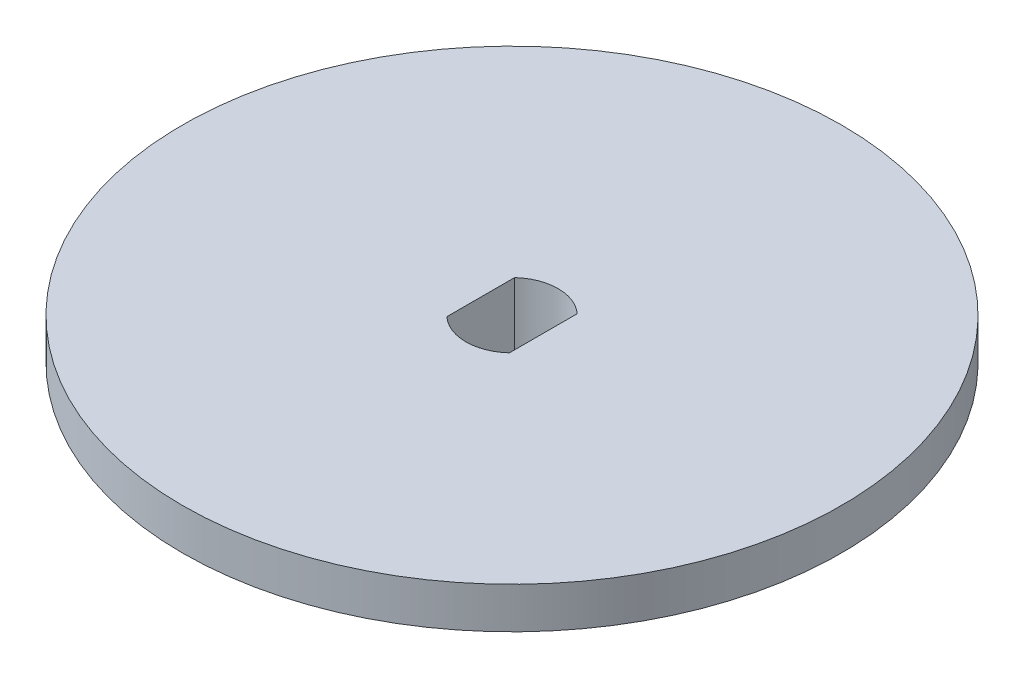
SolidWorks part; units mm, degrees
ref_plane "Front Plane" through (0, 0, 0) normal (0, 0, 1) x (1, 0, 0)
ref_plane "Top Plane" through (0, 0, 0) normal (0, 1, 0) x (1, 0, 0)
ref_plane "Right Plane" through (0, 0, 0) normal (1, 0, 0) x (0, 0, -1)
sketch "Sketch1" plane through (0, 0, 0) normal (0, 1, 0) x (1, 0, 0)
  line L0 (1.9, 2.0567) -> (1.9, -2.0567)
  line L1 (-1.9, -2.0567) -> (-1.9, 2.0567)
  line L2 (-1.9, 2.0567) -> (-1.9, 5.5329)
  line L3 (1.9, 2.0567) -> (1.9, 5.5329)
  line L4 (-1.9, -2.0567) -> (-1.9, -5.5329)
  line L5 (1.9, -2.0567) -> (1.9, -5.5329)
  circle A0 centre (0, 0) radius 2.8
  circle A1 centre (0, 0) radius 5.85
  point P12 (0, 0)
  point P13 (0, 0)
  point P14 (0, 0)
  point P15 (0, 0)
  point P16 (0, 0)
  point P17 (0, 0)
  dimension "D1" = 5.6
  dimension "D4" = 11.7
  dimension "D2" = 1.9
  dimension "D3" = 1.9
extrude "Boss-Extrude1" add sketch "Sketch1" along normal blind 5.5 contours L2 A1 L4 A0 | L3 A1 L2 A0 | L5 A1 L3 A0 | L4 A1 L5 A0 | L1 A0 | L0 A0
sketch "Sketch2" plane through (0, 5.5, 0) normal (0, 1, 0) x (1, 0, 0)
  circle A0 centre (0, 0) radius 20
  dimension "D1" = 40
extrude "Boss-Extrude2" add sketch "Sketch2" against normal blind 2.5
sketch "Sketch3" plane through (0, 3, 0) normal (0, -1, 0) x (1, 0, 0)
  line L2 (-1.9, 2.0567) -> (-1.9, -2.0567)
  line L3 (1.9, -2.0567) -> (1.9, 2.0567)
  line L4 (-1.9, 2.0567) -> (-1.9, -2.0567)
  line L5 (1.9, -2.0567) -> (1.9, 2.0567)
  arc A2 (1.9, 2.0567) -> (-1.9, 2.0567) centre (0, 0) ccw
  arc A3 (-1.9, -2.0567) -> (1.9, -2.0567) centre (0, 0) ccw
  arc A4 (1.9, 2.0567) -> (-1.9, 2.0567) centre (0, 0) ccw
  arc A5 (-1.9, -2.0567) -> (1.9, -2.0567) centre (0, 0) ccw
  dimension "D1" = 0
extrude "Cut-Extrude1" cut sketch "Sketch3" against normal blind 8
